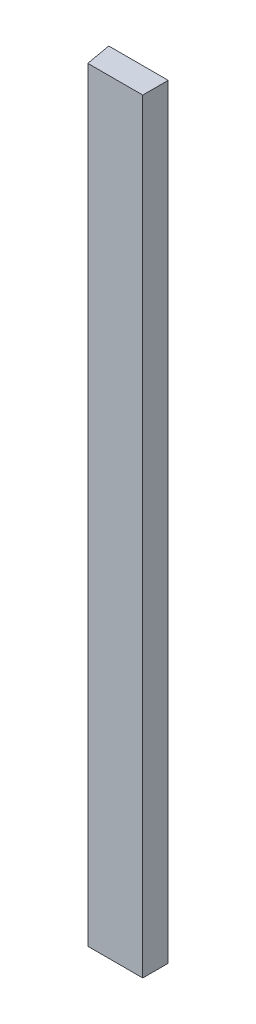
SolidWorks part; units mm, degrees
ref_plane "Front" through (0, 0, 0) normal (0, 0, 1) x (1, 0, 0)
ref_plane "Top" through (0, 0, 0) normal (0, 1, 0) x (1, 0, 0)
ref_plane "Right" through (0, 0, 0) normal (1, 0, 0) x (0, 0, -1)
sketch "Sketch1" plane through (0, 0, 0) normal (0, 1, 0) x (1, 0, 0)
  line L0 (-44.45, 19.05) -> (-37.7319, -19.05)
  line L1 (44.45, 19.05) -> (-44.45, 19.05)
  line L2 (44.45, 19.05) -> (44.45, -19.05)
  line L3 (44.45, -19.05) -> (-37.7319, -19.05)
  line L4 (-44.45, 19.05) -> (-44.45, -19.05) construction
  line L5 (44.45, 19.05) -> (-44.45, -19.05) construction
  line L6 (44.45, -19.05) -> (-44.45, 19.05) construction
  line L7 (-37.7319, -19.05) -> (-44.45, -19.05) construction
  point P0 (0, 0)
  dimension "D1" = 38.1
  dimension "D2" = 88.9
  dimension "D3" = 80
extrude "Boss-Extrude1" add sketch "Sketch1" along normal blind 1143
fillet "Fillet2" [suppressed] radius 3.175
